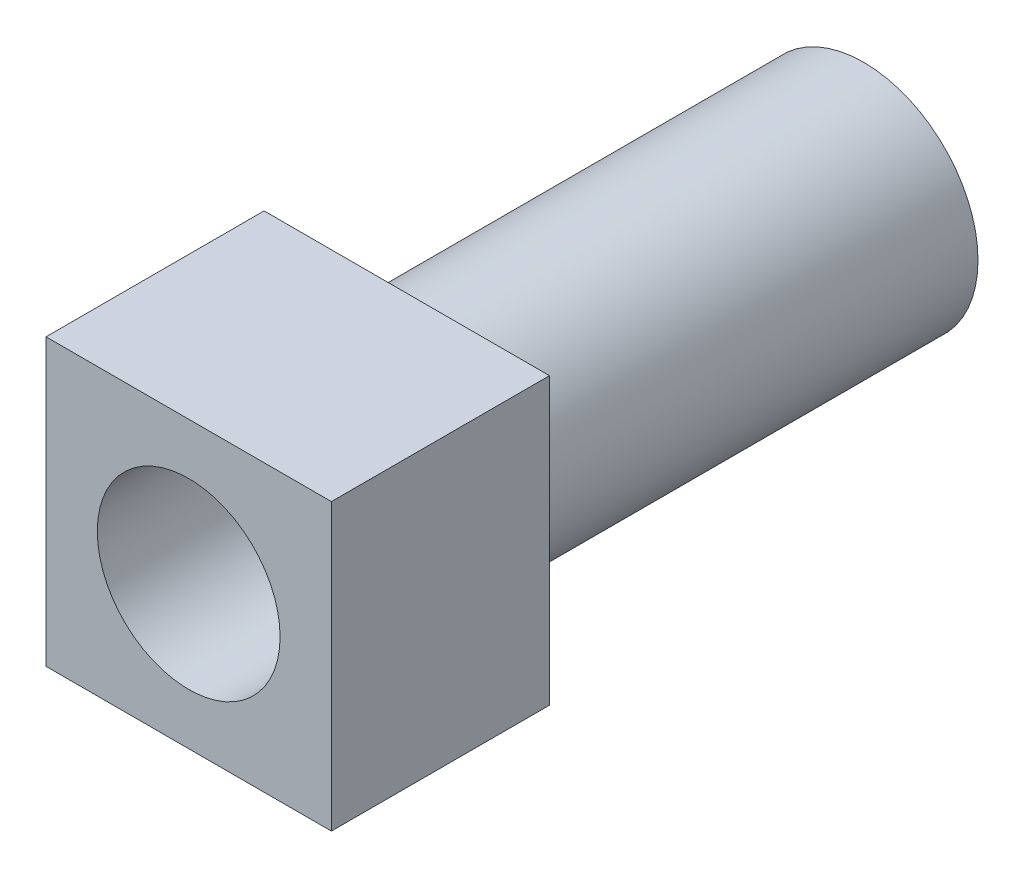
SolidWorks part; units mm, degrees
ref_plane "Plan de face" through (0, 0, 0) normal (0, 0, 1) x (1, 0, 0)
ref_plane "Plan de dessus" through (0, 0, 0) normal (0, 1, 0) x (1, 0, 0)
ref_plane "Plan de droite" through (0, 0, 0) normal (1, 0, 0) x (0, 0, -1)
sketch "Esquisse1" plane through (0, 0, 0) normal (0, 0, 1) x (1, 0, 0)
  line L1 (-37.0561, 15.4804) -> (-23.3161, 15.4804)
  line L2 (-37.0561, 15.4804) -> (-37.0561, 1.7404)
  line L3 (-37.0561, 1.7404) -> (-23.3161, 1.7404)
  line L4 (-23.3161, 15.4804) -> (-23.3161, 1.7404)
  dimension "D1" = 13.74
  dimension "D2" = 13.74
extrude "Boss.-Extru.1" add sketch "Esquisse1" along normal blind 10.5
sketch "Esquisse2" plane through (0, 0, 0) normal (0, 0, -1) x (-1, 0, 0)
  circle A1 centre (30.1861, 8.6104) radius 2.8
sketch "Esquisse3" plane through (0, 0, 10.5) normal (0, 0, 1) x (1, 0, 0)
  circle A0 centre (-30.1861, 8.6104) radius 4.4
extrude "Enlèv. mat.-Extru.2" cut sketch "Esquisse3" against normal blind 10
sketch "Esquisse6" [suppressed] plane through (0, 0, 0) normal (0, 0, -1) x (-1, 0, 0)
  circle A0 centre (30.1861, 8.6104) radius 5.5
  circle A2 centre (30.1861, 8.6104) radius 2.49
sketch "Esquisse8" plane through (0, 0, 0) normal (0, 0, -1) x (-1, 0, 0)
  circle A0 centre (30.1861, 8.6104) radius 5.5
extrude "Boss.-Extru.2" add sketch "Esquisse8" along normal blind 22
extrude "Enlèv. mat.-Extru.3" cut sketch "Esquisse2" along normal blind 22 contours A1
sketch "Esquisse9" plane through (0, 0, -22) normal (0, 0, -1) x (-1, 0, 0)
  line L0 (32.5589, 10.0969) -> (28.8814, 11.0879)
  circle A0 centre (30.1861, 8.6104) radius 2.8 construction
  arc A1 (32.5589, 10.0969) -> (28.8814, 11.0879) centre (30.204, 8.6768) ccw
extrude "Boss.-Extru.3" add sketch "Esquisse9" against normal blind 22
